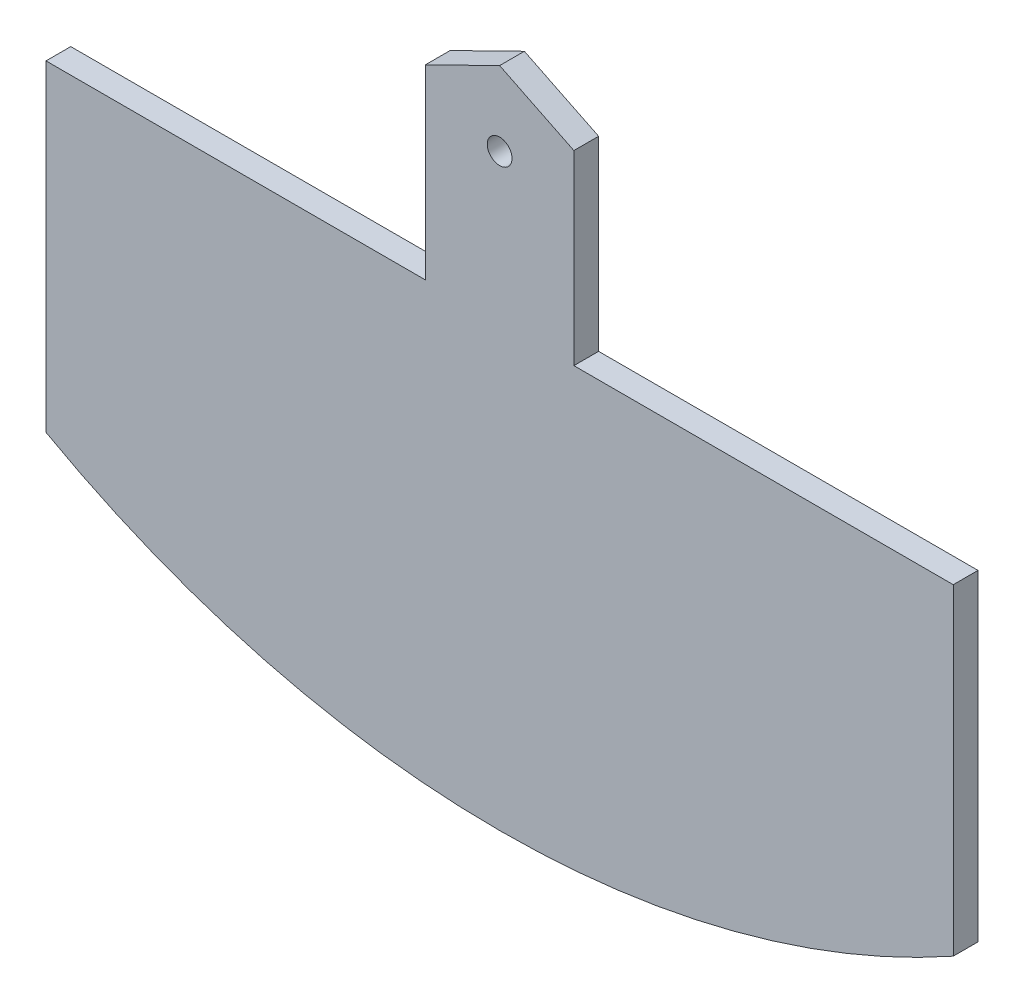
SolidWorks part; units mm, degrees
ref_plane "Přední rovina" through (0, 0, 0) normal (0, 0, 1) x (1, 0, 0)
ref_plane "Horní rovina" through (0, 0, 0) normal (0, 1, 0) x (1, 0, 0)
ref_plane "Pravá rovina" through (0, 0, 0) normal (1, 0, 0) x (0, 0, -1)
sketch "Skica1" plane through (0, 0, 0) normal (0, 0, 1) x (1, 0, 0)
  line L0 (-91.6461, -95) -> (91.6461, -95)
  line L1 (0, 15) -> (91.6461, -30)
  line L2 (91.6461, -30) -> (91.6461, -95)
  line L3 (0, 15) -> (-91.6461, -30)
  line L4 (-91.6461, -30) -> (-91.6461, -95)
  dimension "D1" = 183.2921
  dimension "D2" = 15
  dimension "D3" = 102.098
  dimension "D4" = 65
  dimension "D5" = 65
  dimension "D6" = 102.098
extrude "Přidat vysunutím1" add sketch "Skica1" along normal blind 5
sketch "Skica2" plane through (0, 0, 5) normal (0, 0, 1) x (1, 0, 0)
  circle A0 centre (0, 0) radius 2.5
  dimension "D1" = 5
extrude "Odebrat vysunutím1" cut sketch "Skica2" against normal blind 5
sketch "Skica3" plane through (0, 0, 5) normal (0, 0, 1) x (1, 0, 0)
  line L0 (91.6461, -30) -> (15, -30)
  line L1 (15, -30) -> (15, 7.6347)
  line L2 (91.6461, -30) -> (0, 15) construction
  line L3 (15, 7.6347) -> (91.6461, -30)
  line L6 (0, 0) -> (0, -23.556) construction
  line L7 (-15, 7.6347) -> (-91.6461, -30)
  line L8 (-15, -30) -> (-15, 7.6347)
  line L9 (-91.6461, -30) -> (-15, -30)
  dimension "D1" = 15
extrude "Odebrat vysunutím2" cut sketch "Skica3" against normal blind 5
sketch "Skica4" plane through (0, 0, 5) normal (0, 0, 1) x (1, 0, 0)
  line L9 (91.6461, -30) -> (15, -30)
  line L10 (15, -30) -> (15, 7.6347)
  line L11 (15, 7.6347) -> (0, 15)
  line L12 (0, 15) -> (-15, 7.6347)
  line L13 (-15, 7.6347) -> (-15, -30)
  line L14 (-15, -30) -> (-91.6461, -30)
  line L15 (-91.6461, -30) -> (-91.6461, -95)
  line L16 (-91.6461, -95) -> (91.6461, -95)
  line L17 (91.6461, -95) -> (91.6461, -30)
  line L25 (-91.6461, -95) -> (91.6461, -95)
  arc A0 (-91.6461, -95) -> (91.6461, -95) centre (0, 69.1701) ccw
  dimension "D1" = 188.0182
  dimension "D2" = 0
extrude "Přidat vysunutím2" add sketch "Skica4" against normal blind 5
